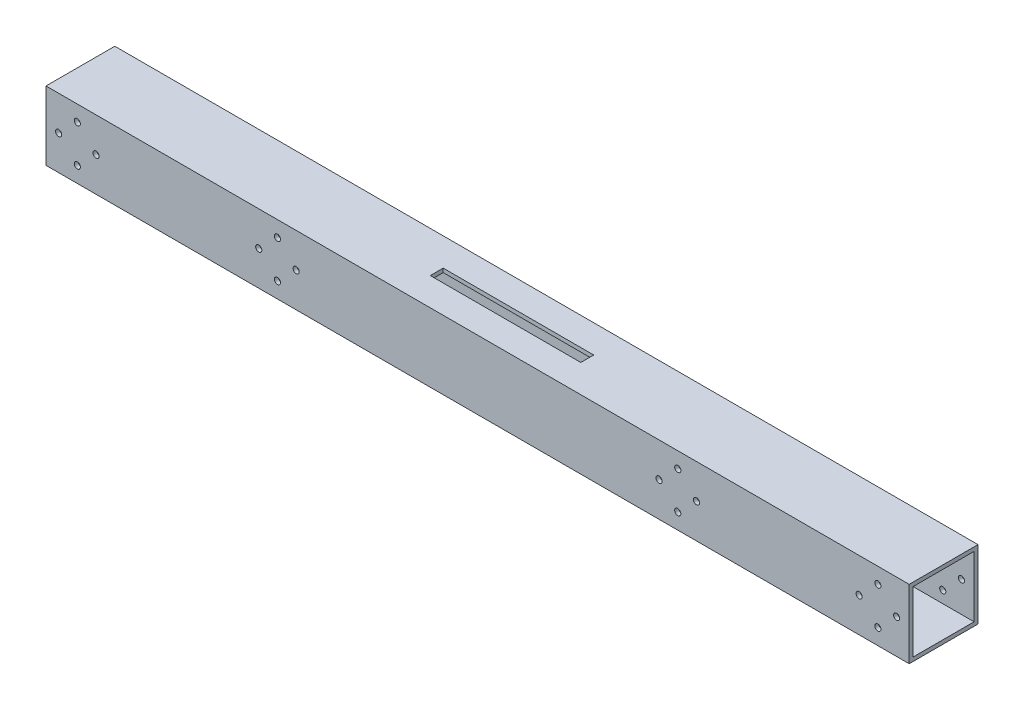
SolidWorks part; units mm, degrees
ref_plane "Front Plane" through (0, 0, 0) normal (0, 0, 1) x (1, 0, 0)
ref_plane "Top Plane" through (0, 0, 0) normal (0, 1, 0) x (1, 0, 0)
ref_plane "Right Plane" through (0, 0, 0) normal (1, 0, 0) x (0, 0, -1)
sketch "Sketch1" plane through (0, 0, 0) normal (1, 0, 0) x (0, 0, -1)
  line L1 (-17.4625, -17.4625) -> (17.4625, -17.4625)
  line L2 (-17.4625, -17.4625) -> (-17.4625, 17.4625)
  line L3 (-17.4625, 17.4625) -> (17.4625, 17.4625)
  line L4 (17.4625, -17.4625) -> (17.4625, 17.4625)
  line L5 (-17.4625, -17.4625) -> (17.4625, 17.4625) construction
  line L6 (-17.4625, 17.4625) -> (17.4625, -17.4625) construction
  line L7 (-15.4813, -15.4813) -> (15.4813, -15.4813)
  line L8 (-15.4813, -15.4813) -> (-15.4813, 15.4813)
  line L9 (-15.4813, 15.4813) -> (15.4813, 15.4813)
  line L10 (15.4813, -15.4813) -> (15.4813, 15.4813)
  line L11 (-15.4813, -15.4813) -> (15.4813, 15.4813) construction
  line L12 (-15.4813, 15.4813) -> (15.4813, -15.4813) construction
  point P0 (0, 0)
  point P5 (0, 0)
  dimension "D1" = 34.925
  dimension "D2" = 30.9626
extrude "Boss-Extrude1" add sketch "Sketch1" along normal mid plane 438.15
sketch "Sketch2" plane through (0, 17.4625, 0) normal (0, 1, 0) x (1, 0, 0)
  line L1 (-38.2, -3.275) -> (38.2, -3.275)
  line L2 (-38.2, -3.275) -> (-38.2, 3.275)
  line L3 (-38.2, 3.275) -> (38.2, 3.275)
  line L4 (38.2, -3.275) -> (38.2, 3.275)
  line L5 (-38.2, -3.275) -> (38.2, 3.275) construction
  line L6 (-38.2, 3.275) -> (38.2, -3.275) construction
  point P0 (0, 0)
  dimension "D1" = 6.55
  dimension "D2" = 76.4
extrude "Cut-Extrude1" cut sketch "Sketch2" against normal through all
sketch "Sketch5" plane through (0, 0, 0) normal (0, 0, 1) x (1, 0, 0)
  line L0 (-203.175, 9.5) -> (-203.175, -9.5) construction
  line L1 (-219.075, 17.4625) -> (-219.075, -17.4625) construction
  line L2 (-212.675, 0) -> (-193.675, 0) construction
  line L4 (0, -55) -> (0, 55) construction
  line L5 (212.675, 0) -> (193.675, 0) construction
  line L6 (203.175, 9.5) -> (203.175, -9.5) construction
  circle A0 centre (-203.175, 9.5) radius 1.5625
  circle A1 centre (-193.675, 0) radius 1.5625
  circle A2 centre (-203.175, -9.5) radius 1.5625
  circle A3 centre (-212.675, 0) radius 1.5625
  circle A4 centre (212.675, 0) radius 1.5625
  circle A5 centre (203.175, -9.5) radius 1.5625
  circle A6 centre (193.675, 0) radius 1.5625
  circle A7 centre (203.175, 9.5) radius 1.5625
  point P6 (-203.175, 0)
  point P7 (-203.175, 0)
  dimension "D3" = 3.125
  dimension "D1" = 19
  dimension "D2" = 25.4
extrude "Cut-Extrude3" cut sketch "Sketch5" against normal through all and the other way through all
sketch "Sketch6" plane through (0, 0, 17.4625) normal (0, 0, 1) x (1, 0, 0)
  line L0 (-101.6, 9.5) -> (-101.6, -9.5) construction
  line L1 (-111.1, 0) -> (-92.1, 0) construction
  circle A0 centre (-101.6, 9.5) radius 1.5625
  circle A1 centre (-92.1, 0) radius 1.5625
  circle A2 centre (-101.6, -9.5) radius 1.5625
  circle A3 centre (-111.1, 0) radius 1.5625
  point P4 (-101.6, 0)
  point P5 (-101.6, 0)
  dimension "D2" = 3.125
  dimension "D1" = 19
  dimension "D3" = 101.6
extrude "Cut-Extrude5" cut sketch "Sketch6" against normal through all
mirror "Mirror1" about plane through (0, 0, 0) normal (1, 0, 0) of "Cut-Extrude5"
equation "\"D1@Sketch2\"=\"sheet thickness\" + \"tolerance\""
equation "\"D2@Sketch1\"=\"id\""
equation "\"D1@Sketch1\"=\"od\""
equation "\"od\"= 1.375in"
equation "\"id\"= \"od\" - ( .078in * 2 )"
equation "\"length\"= 20in"
equation "\"tolerance\"= .2mm"
equation "\"D1@Boss-Extrude1\"=\"length\"-(\"od\"*2)"
equation "\"sheet thickness\"= .25in"
equation "\"slot width\"= 3in"
equation "\"D2@Sketch2\"=\"slot width\"+\"tolerance\""
equation "\"thruster hole (oversized)\"= 3.125mm"
equation "\"D3@Sketch5\"=\"thruster hole (oversized)\""
